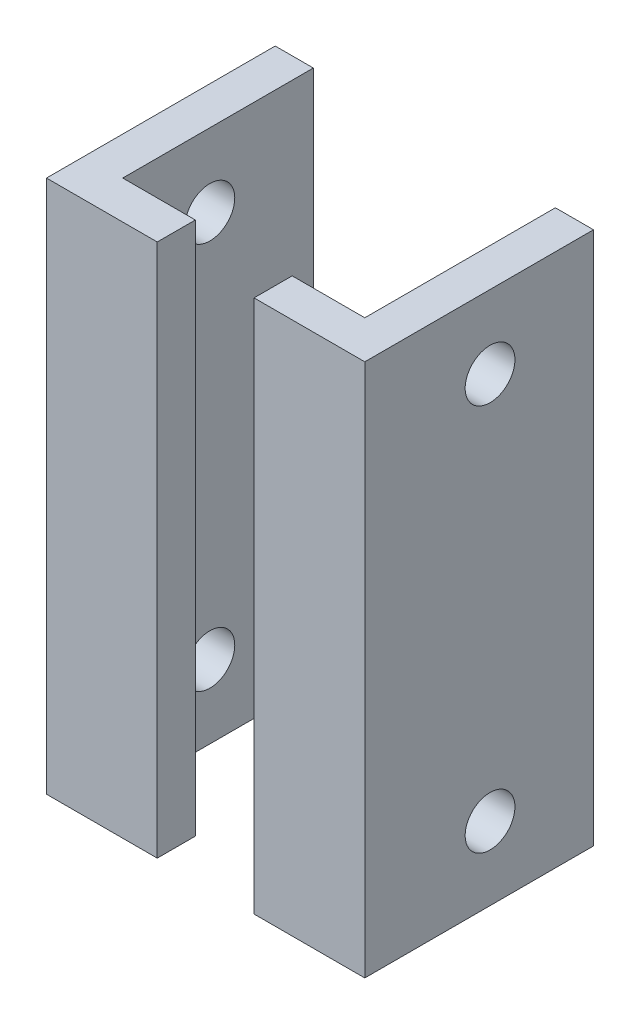
SolidWorks part; units mm, degrees
material "PBT General Purpose"
ref_plane "Front Plane" through (0, 0, 0) normal (0, 0, 1) x (1, 0, 0)
ref_plane "Top Plane" through (0, 0, 0) normal (0, 1, 0) x (1, 0, 0)
ref_plane "Right Plane" through (0, 0, 0) normal (1, 0, 0) x (0, 0, -1)
sketch "Sketch1" plane through (15.875, 0, 0) normal (1, 0, 0) x (0, 0, -1)
  line L0 (-49.45, 314.4) -> (-19.45, 314.4)
  line L1 (-19.45, 314.4) -> (-19.45, 244.4)
  line L2 (-19.45, 244.4) -> (-49.45, 244.4)
  line L3 (-49.45, 244.4) -> (-49.45, 314.4)
  line L4 (-33.02, 304.8) -> (-33.02, 254) construction
  line L5 (-19.45, 279.4) -> (-49.45, 279.4) construction
  line L6 (-44.45, 313.7636) -> (-44.45, 245.0364) construction
  circle A0 centre (-33.02, 254) radius 3.2639 construction
  circle A1 centre (-33.02, 304.8) radius 3.2639 construction
  circle A2 centre (-33.02, 254) radius 3.2639
  circle A3 centre (-33.02, 304.8) radius 3.2639
  point P14 (-33.02, 279.4)
  dimension "D1" = 25
  dimension "D2" = 5
  dimension "D3" = 70
extrude "Boss-Extrude1" add sketch "Sketch1" along normal blind 5
sketch "Sketch2" plane through (15.875, 0, 0) normal (-1, 0, 0) x (0, 0, 1)
  line L0 (49.45, 314.4) -> (49.45, 244.4) construction
  line L1 (49.45, 314.4) -> (49.45, 244.4)
  line L2 (49.45, 314.4) -> (44.45, 314.4)
  line L3 (19.45, 314.4) -> (49.45, 314.4) construction
  line L4 (44.45, 314.4) -> (44.45, 244.4)
  line L5 (49.45, 244.4) -> (19.45, 244.4) construction
  line L6 (44.45, 244.4) -> (49.45, 244.4)
  line L7 (44.45, 254) -> (44.45, 304.8) construction
extrude "Boss-Extrude2" add sketch "Sketch2" along normal up to surface (9.525 mm away)
mirror "Mirror2" about plane through (0, 0, 0) normal (1, 0, 0) of bodies 102
